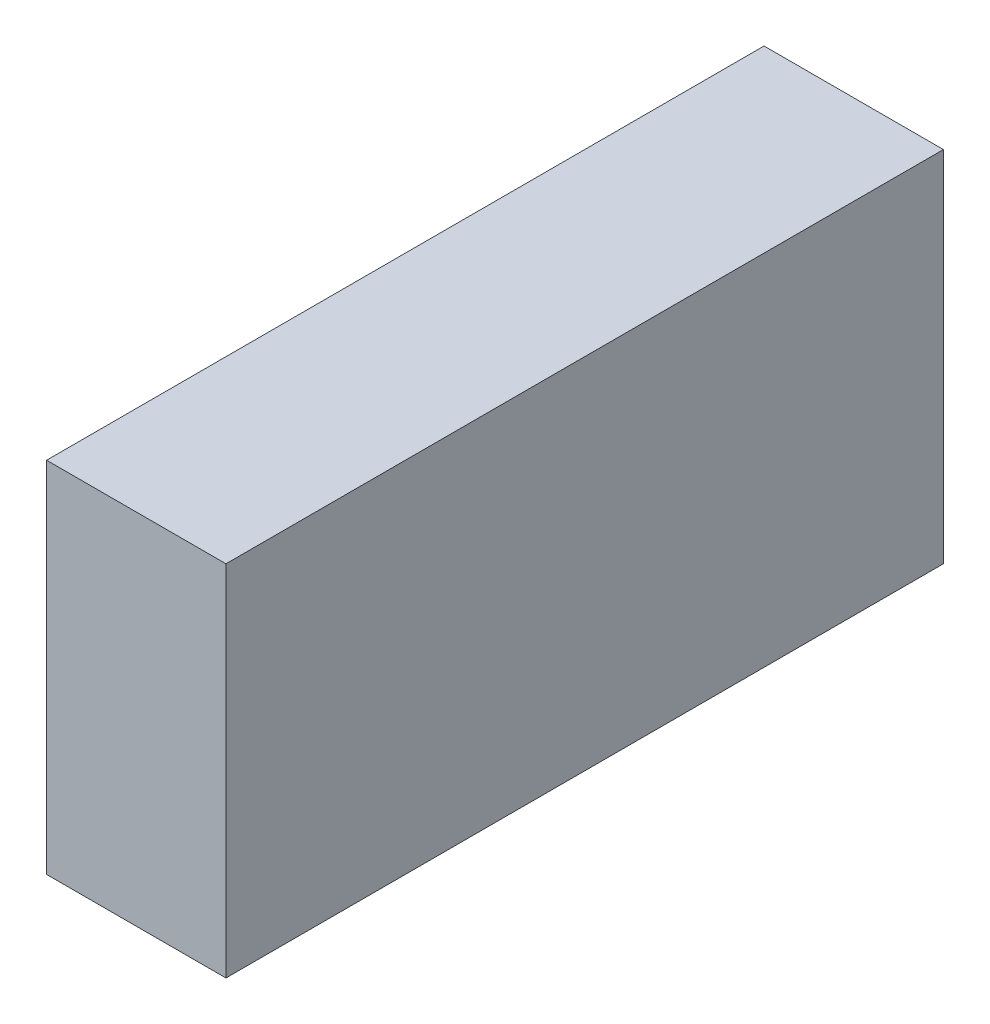
SolidWorks part; units mm, degrees
ref_plane "Front Plane" through (0, 0, 0) normal (0, 0, 1) x (1, 0, 0)
ref_plane "Top Plane" through (0, 0, 0) normal (0, 1, 0) x (1, 0, 0)
ref_plane "Right Plane" through (0, 0, 0) normal (1, 0, 0) x (0, 0, -1)
sketch "Sketch1" plane through (0, 0, 0) normal (1, 0, 0) x (0, 0, -1)
  line L1 (0, 0) -> (40, 0)
  line L2 (0, 0) -> (0, 20)
  line L3 (0, 20) -> (40, 20)
  line L4 (40, 0) -> (40, 20)
extrude "Boss-Extrude1" add sketch "Sketch1" along normal blind 10
